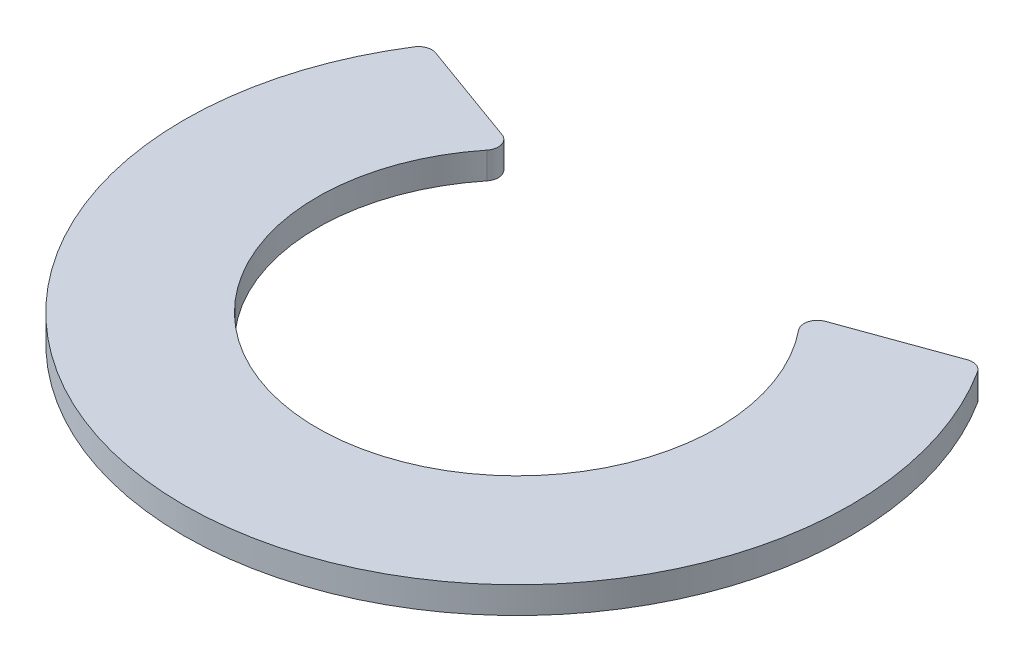
SolidWorks part; units mm, degrees
ref_plane "Alzado" through (0, 0, 0) normal (0, 0, 1) x (1, 0, 0)
ref_plane "Planta" through (0, 0, 0) normal (0, 1, 0) x (1, 0, 0)
ref_plane "Vista lateral" through (0, 0, 0) normal (1, 0, 0) x (0, 0, -1)
sketch "Croquis1" plane through (0, 0, 0) normal (0, 1, 0) x (1, 0, 0)
  line L0 (-1.9925, 1.3798) -> (-1.2122, 1.0975)
  line L1 (1.2122, 1.0975) -> (1.9925, 1.3798)
  arc A0 (-1.1683, 0.9408) -> (1.1683, 0.9408) centre (0, 0) ccw
  arc A1 (-2.111, 1.3393) -> (2.111, 1.3393) centre (0, 0) ccw
  arc A2 (2.111, 1.3393) -> (1.9925, 1.3798) centre (2.0265, 1.2857) ccw
  arc A3 (1.1683, 0.9408) -> (1.2122, 1.0975) centre (1.2462, 1.0035) cw
  arc A4 (-1.1683, 0.9408) -> (-1.2122, 1.0975) centre (-1.2462, 1.0035) ccw
  arc A5 (-2.111, 1.3393) -> (-1.9925, 1.3798) centre (-2.0265, 1.2857) cw
  point P8 (2.0667, 1.4066)
  point P11 (1.0737, 1.0474)
  point P14 (-1.0737, 1.0474)
  point P17 (-2.0667, 1.4066)
  point P18 (0, 0)
  point P19 (0, 0)
  point P20 (0, 0)
  dimension "D1" = 2.5
  dimension "D2" = 1.5
  dimension "D3" = 0.1
extrude "Saliente-Extruir1" add sketch "Croquis1" along normal blind 0.2
